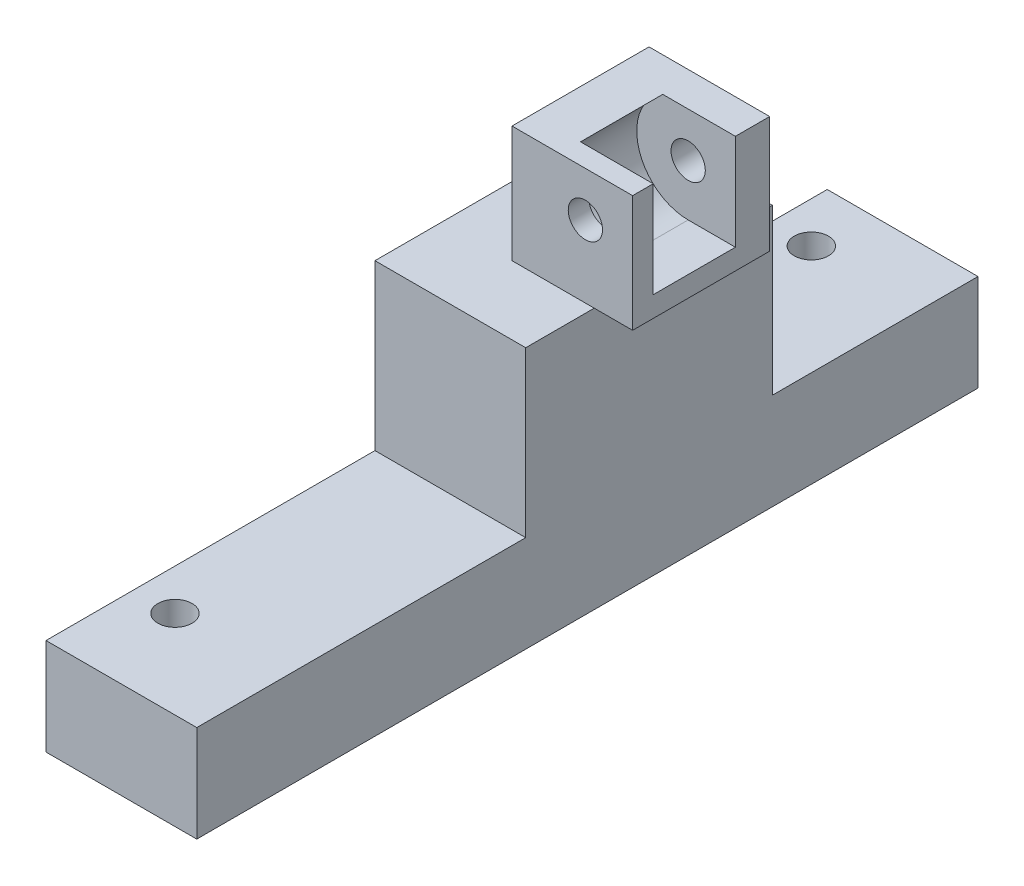
SolidWorks part; units mm, degrees
ref_plane "Front Plane" through (0, 0, 0) normal (0, 0, 1) x (1, 0, 0)
ref_plane "Top Plane" through (0, 0, 0) normal (0, 1, 0) x (1, 0, 0)
ref_plane "Right Plane" through (0, 0, 0) normal (1, 0, 0) x (0, 0, -1)
sketch "Sketch1" plane through (0, 0, 0) normal (0, 0, 1) x (1, 0, 0)
  line L0 (-792.5838, 356.7694) -> (-801.3383, 356.7694)
  line L1 (-814.9358, 374.5748) -> (-792.5838, 374.5748)
  line L2 (-814.9358, 374.5748) -> (-814.9358, 352.9594)
  line L3 (-814.9358, 352.9594) -> (-792.5838, 352.9594)
  line L4 (-792.5838, 374.5748) -> (-792.5838, 352.9594)
  circle A0 centre (-801.3383, 366.2944) radius 3.175
  arc A1 (-801.3383, 356.7694) -> (-806.0458, 358.014) centre (-801.3383, 366.2944) cw
  arc A2 (-806.0458, 358.014) -> (-806.0458, 374.5748) centre (-801.3383, 366.2944) cw
  dimension "D1" = 6.35
extrude "Boss-Extrude1" add sketch "Sketch1" against normal blind 21.59 contours A1 A2 L1 L2 L3 L4 L0
sketch "Sketch2" plane through (0, 0, 0) normal (0, 0, 1) x (1, 0, 0)
  line L0 (-800.9658, 352.9594) -> (-828.9058, 352.9594) construction
  line L1 (-814.9358, 352.9594) -> (-792.5838, 352.9594)
  line L2 (-814.9358, 352.9594) -> (-814.9358, 374.5748)
  line L3 (-814.9358, 374.5748) -> (-792.5838, 374.5748)
  line L4 (-792.5838, 352.9594) -> (-792.5838, 374.5748)
  circle A0 centre (-801.3383, 366.2944) radius 3.175
  dimension "D1" = 6.35
extrude "Boss-Extrude2" add sketch "Sketch2" along normal blind 3.81
sketch "Sketch3" plane through (0, 0, -21.59) normal (0, 0, -1) x (-1, 0, 0)
  line L0 (792.5838, 356.7694) -> (792.5838, 374.5748)
  line L1 (792.5838, 374.5748) -> (806.0458, 374.5748)
  line L2 (792.5838, 356.7694) -> (801.3383, 356.7694)
  arc A0 (806.0458, 374.5748) -> (801.3383, 356.7694) centre (801.3383, 366.2944) cw
  circle A1 centre (801.3383, 366.2944) radius 3.175
  dimension "D1" = 6.35
  dimension "D2" = 9.525
extrude "Boss-Extrude3" add sketch "Sketch3" against normal offset from surface (6.35 mm away) 3.81
sketch "Sketch4" plane through (0, 352.9594, 0) normal (0, -1, 0) x (1, 0, 0)
  line L1 (-799.6958, 77.47) -> (-827.6358, 77.47)
  line L2 (-799.6958, 77.47) -> (-799.6958, -67.31)
  line L3 (-799.6958, -67.31) -> (-827.6358, -67.31)
  line L4 (-827.6358, 77.47) -> (-827.6358, -67.31)
  circle A0 centre (-820.039, -56.7657) radius 3.175
  circle A1 centre (-820.039, 61.1629) radius 3.175
  dimension "D5" = 6.35
  dimension "D6" = 6.35
  dimension "D1" = 27.94
  dimension "D2" = 45.72
  dimension "D3" = 73.66
  dimension "D4" = 12.7
extrude "Boss-Extrude4" add sketch "Sketch4" along normal up to surface (48.388 mm away) contours L2 L1 L4 L3
sketch "Sketch5" plane through (-827.6358, 0, 0) normal (-1, 0, 0) x (0, 0, 1)
  line L0 (77.47, 352.9594) -> (-67.31, 352.9594) construction
  line L1 (-67.31, 352.9594) -> (-29.21, 352.9594)
  line L2 (-67.31, 352.9594) -> (-67.31, 322.4794)
  line L3 (-67.31, 322.4794) -> (-29.21, 322.4794)
  line L4 (-29.21, 352.9594) -> (-29.21, 322.4794)
  line L5 (16.51, 352.9594) -> (77.47, 352.9594)
  line L6 (16.51, 352.9594) -> (16.51, 322.4794)
  line L7 (16.51, 322.4794) -> (77.47, 322.4794)
  line L8 (77.47, 352.9594) -> (77.47, 322.4794)
  line L9 (77.47, 304.5714) -> (77.47, 352.9594) construction
  dimension "D1" = 30.48
  dimension "D2" = 30.48
  dimension "D3" = 38.1
  dimension "D4" = 60.96
extrude "Cut-Extrude1" cut sketch "Sketch5" against normal through all
sketch "Sketch6" plane through (0, 322.4794, 0) normal (0, 1, 0) x (1, 0, 0)
  circle A0 centre (-820.039, 56.7657) radius 3.175
  circle A1 centre (-820.039, -61.1629) radius 3.175
  circle A2 centre (-820.039, 56.7657) radius 3.175 construction
  dimension "D1" = 6.35
  dimension "D2" = 6.35
extrude "Cut-Extrude2" cut sketch "Sketch6" against normal through all
